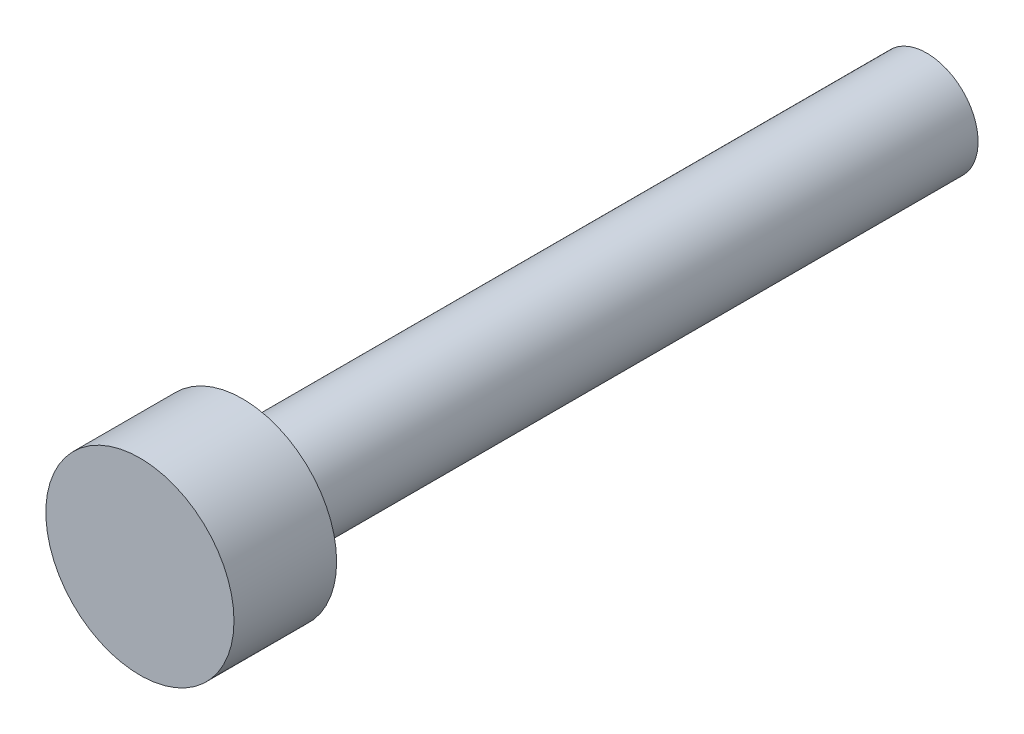
SolidWorks part; units mm, degrees
ref_plane "Front Plane" through (0, 0, 0) normal (0, 0, 1) x (1, 0, 0)
ref_plane "Top Plane" through (0, 0, 0) normal (0, 1, 0) x (1, 0, 0)
ref_plane "Right Plane" through (0, 0, 0) normal (1, 0, 0) x (0, 0, -1)
sketch "Sketch1" plane through (0, 0, 0) normal (0, 0, 1) x (1, 0, 0)
  circle A0 centre (0, 0) radius 2.75
  dimension "D1" = 5.5
extrude "Boss-Extrude1" add sketch "Sketch1" along normal blind 3
sketch "Sketch2" plane through (0, 0, 0) normal (0, 0, -1) x (-1, 0, 0)
  circle A0 centre (0, 0) radius 1.5
  dimension "D1" = 3
extrude "Boss-Extrude2" add sketch "Sketch2" along normal blind 20
